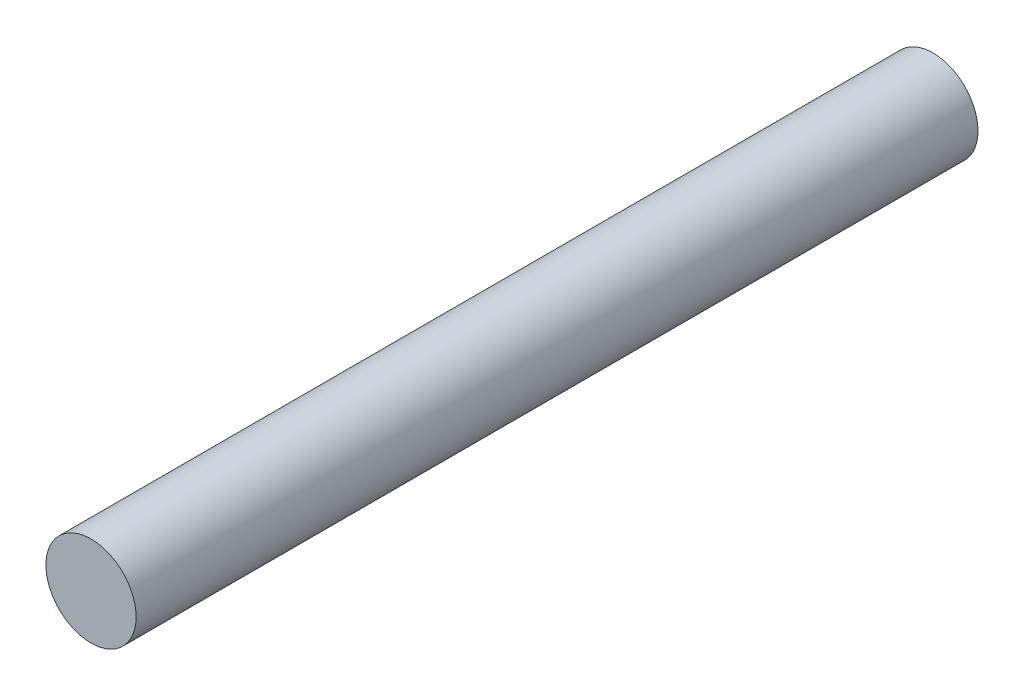
SolidWorks part; units mm, degrees
ref_plane "前视基准面" through (0, 0, 0) normal (0, 0, 1) x (1, 0, 0)
ref_plane "上视基准面" through (0, 0, 0) normal (0, 1, 0) x (1, 0, 0)
ref_plane "右视基准面" through (0, 0, 0) normal (1, 0, 0) x (0, 0, -1)
sketch "草图2" plane through (0, 0, 0) normal (0, 0, 1) x (1, 0, 0)
  circle A0 centre (-52.449, 6.9484) radius 15
extrude "凸台-拉伸2" add sketch "草图2" along normal blind 280
